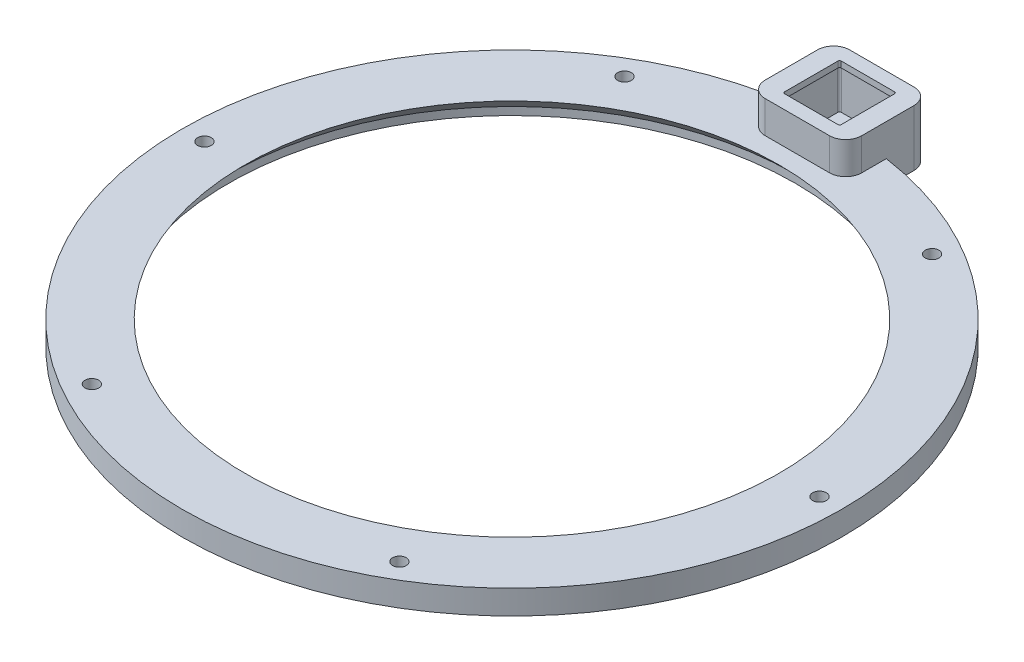
SolidWorks part; units mm, degrees
ref_plane "Front Plane" through (0, 0, 0) normal (0, 0, 1) x (1, 0, 0)
ref_plane "Top Plane" through (0, 0, 0) normal (0, 1, 0) x (1, 0, 0)
ref_plane "Right Plane" through (0, 0, 0) normal (1, 0, 0) x (0, 0, -1)
sketch "Sketch1" plane through (0, 0, 0) normal (0, 0, 1) x (1, 0, 0)
  line L0 (0, 40) -> (0, 70) construction
  line L1 (70.5, 53) -> (82, 53)
  line L2 (82, 53) -> (82, 59)
  line L3 (82, 59) -> (66.45, 59)
  line L4 (66.45, 59) -> (70.5, 54.95)
  line L5 (70.5, 54.95) -> (70.5, 53)
revolve "Lip ring" add sketch "Sketch1" angle 360 about L0
sketch "Sketch2" plane through (0, 0, 0) normal (0, 1, 0) x (1, 0, 0)
  line L0 (-8, 92) -> (8, 92)
  line L1 (12, 88) -> (12, 75)
  line L2 (8, 71) -> (-8, 71)
  line L3 (-12, 75) -> (-12, 88)
  arc A0 (-12, 88) -> (-8, 92) centre (-8, 88) cw
  arc A1 (8, 92) -> (12, 88) centre (8, 88) cw
  arc A2 (12, 75) -> (8, 71) centre (8, 75) cw
  arc A3 (-8, 71) -> (-12, 75) centre (-8, 75) cw
extrude "MX pod" add sketch "Sketch2" along normal blind 14 from offset 53
sketch "Sketch3" plane through (0, 0, 0) normal (0, 1, 0) x (1, 0, 0)
  line L0 (-6.65, 88.55) -> (6.65, 88.55)
  line L1 (7.05, 88.15) -> (7.05, 74.85)
  line L2 (6.65, 74.45) -> (-6.65, 74.45)
  line L3 (-7.05, 74.85) -> (-7.05, 88.15)
  arc A0 (-7.05, 88.15) -> (-6.65, 88.55) centre (-6.65, 88.15) cw
  arc A1 (6.65, 88.55) -> (7.05, 88.15) centre (6.65, 88.15) cw
  arc A2 (7.05, 74.85) -> (6.65, 74.45) centre (6.65, 74.85) cw
  arc A3 (-6.65, 74.45) -> (-7.05, 74.85) centre (-6.65, 74.85) cw
extrude "MX cutout" cut sketch "Sketch3" along normal blind 1.7 from offset 65.5
sketch "Sketch4" plane through (0, 0, 0) normal (0, 1, 0) x (1, 0, 0)
  line L0 (-7.5, 89.5) -> (7.5, 89.5)
  line L1 (8, 89) -> (8, 74)
  line L2 (7.5, 73.5) -> (-7.5, 73.5)
  line L3 (-8, 74) -> (-8, 89)
  arc A0 (-8, 89) -> (-7.5, 89.5) centre (-7.5, 89) cw
  arc A1 (7.5, 89.5) -> (8, 89) centre (7.5, 89) cw
  arc A2 (8, 74) -> (7.5, 73.5) centre (7.5, 74) cw
  arc A3 (-7.5, 73.5) -> (-8, 74) centre (-7.5, 74) cw
extrude "MX relief" cut sketch "Sketch4" along normal blind 10.5 from offset 55
sketch "Sketch5" plane through (0, 0, 0) normal (0, 1, 0) x (1, 0, 0)
  circle A0 centre (0, 76.5) radius 3.5
extrude "MX lead hole" cut sketch "Sketch5" along normal blind 2.4 from offset 52.8
sketch "Sketch6" plane through (0, 0, 0) normal (0, 1, 0) x (1, 0, 0)
  circle A0 centre (76.5, 0) radius 1.7
  circle A1 centre (38.25, -66.2509) radius 1.7
  circle A2 centre (-38.25, -66.2509) radius 1.7
  circle A3 centre (-76.5, 0) radius 1.7
  circle A4 centre (-38.25, 66.2509) radius 1.7
  circle A5 centre (38.25, 66.2509) radius 1.7
extrude "Bolt holes" cut sketch "Sketch6" along normal blind 6.4 from offset 52.8
